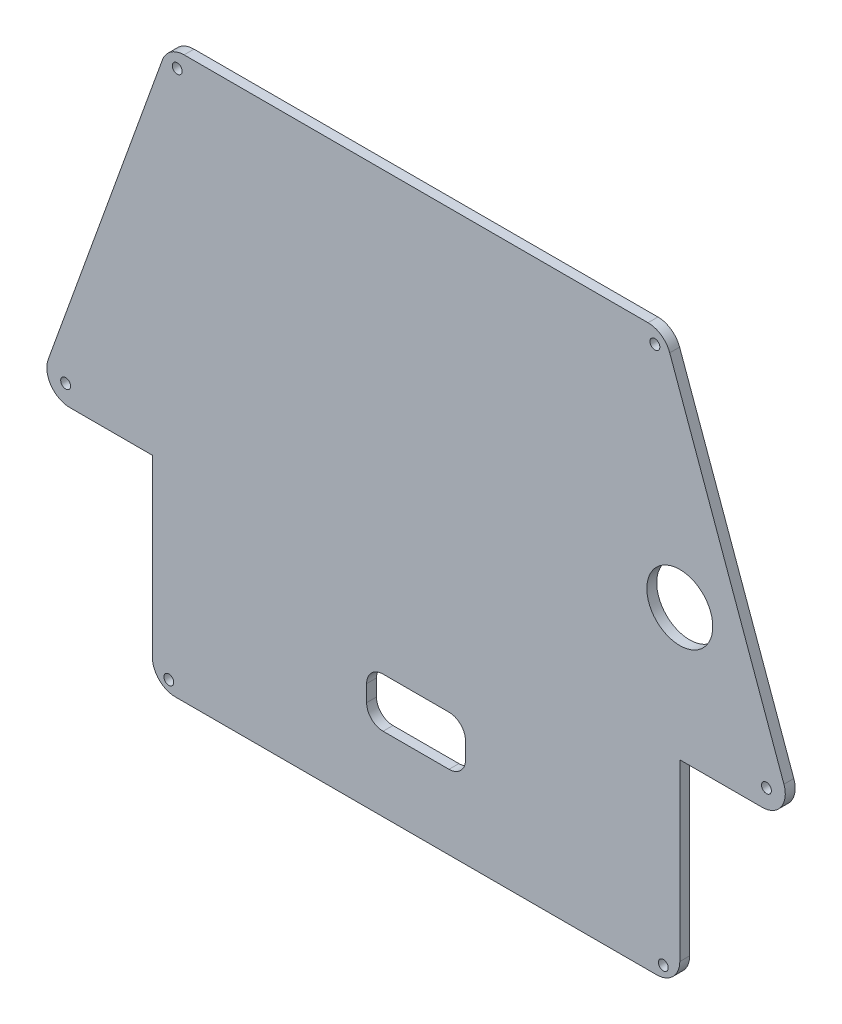
SolidWorks part; units mm, degrees
ref_plane "前视基准面" through (0, 0, 0) normal (0, 0, 1) x (1, 0, 0)
ref_plane "上视基准面" through (0, 0, 0) normal (0, 1, 0) x (1, 0, 0)
ref_plane "右视基准面" through (0, 0, 0) normal (1, 0, 0) x (0, 0, -1)
sketch "草图2" plane through (0, 0, 0) normal (0, 0, 1) x (1, 0, 0)
  line L1 (-73, 0) -> (73, 0)
  line L2 (-50, 40.7094) -> (-50, 5.5717) construction
  line L3 (-70.3629, 170) -> (70.3629, 170)
  line L7 (-80, 7) -> (-80, 60)
  line L8 (-80, 60) -> (-105, 60)
  line L9 (-111.5845, 69.3757) -> (-76.9474, 165.3757)
  line L10 (80, 7) -> (80, 60)
  line L11 (80, 60) -> (105, 60)
  line L12 (111.5845, 69.3757) -> (76.9474, 165.3757)
  line L23 (-10, 22.5) -> (10, 22.5)
  line L24 (-15, 27.5) -> (-15, 32.5)
  line L25 (-10, 37.5) -> (10, 37.5)
  line L26 (15, 27.5) -> (15, 32.5)
  line L27 (-15, 22.5) -> (15, 37.5) construction
  line L28 (-15, 37.5) -> (15, 22.5) construction
  arc A0 (105, 60) -> (111.5845, 69.3757) centre (105, 67) ccw
  arc A1 (73, 0) -> (80, 7) centre (73, 7) ccw
  arc A2 (-105, 60) -> (-111.5845, 69.3757) centre (-105, 67) cw
  arc A3 (-80, 7) -> (-73, 0) centre (-73, 7) ccw
  arc A4 (-76.9474, 165.3757) -> (-70.3629, 170) centre (-70.3629, 163) cw
  arc A5 (76.9474, 165.3757) -> (70.3629, 170) centre (70.3629, 163) ccw
  circle A6 centre (80, 100) radius 10
  circle A14 centre (-72.4414, 165.3757) radius 1.5
  circle A15 centre (-106.2915, 65.7561) radius 1.5
  circle A16 centre (106.2915, 65.7561) radius 1.5
  circle A17 centre (72.4414, 165.3757) radius 1.5
  arc A18 (10, 22.5) -> (15, 27.5) centre (10, 27.5) ccw
  arc A19 (-15, 32.5) -> (-10, 37.5) centre (-10, 32.5) cw
  arc A20 (-10, 22.5) -> (-15, 27.5) centre (-10, 27.5) cw
  arc A21 (10, 37.5) -> (15, 32.5) centre (10, 32.5) cw
  circle A24 centre (-75, 3.552) radius 1.5
  circle A25 centre (75, 3.552) radius 1.5
  point P0 (0, 0)
  point P49 (0, 30)
  dimension "D1" = 170
  dimension "D6" = 30
  dimension "D7" = 5
  dimension "D11" = 3
  dimension "D12" = 3
  dimension "D13" = 7
  dimension "D14" = 7
  dimension "D3" = 20
  dimension "D18" = 3
  dimension "D4" = 40
  dimension "D5" = 30
  dimension "D20" = 160
  dimension "D21" = 150
  dimension "D22" = 25
extrude "凸台-拉伸2" add sketch "草图2" along normal blind 3
